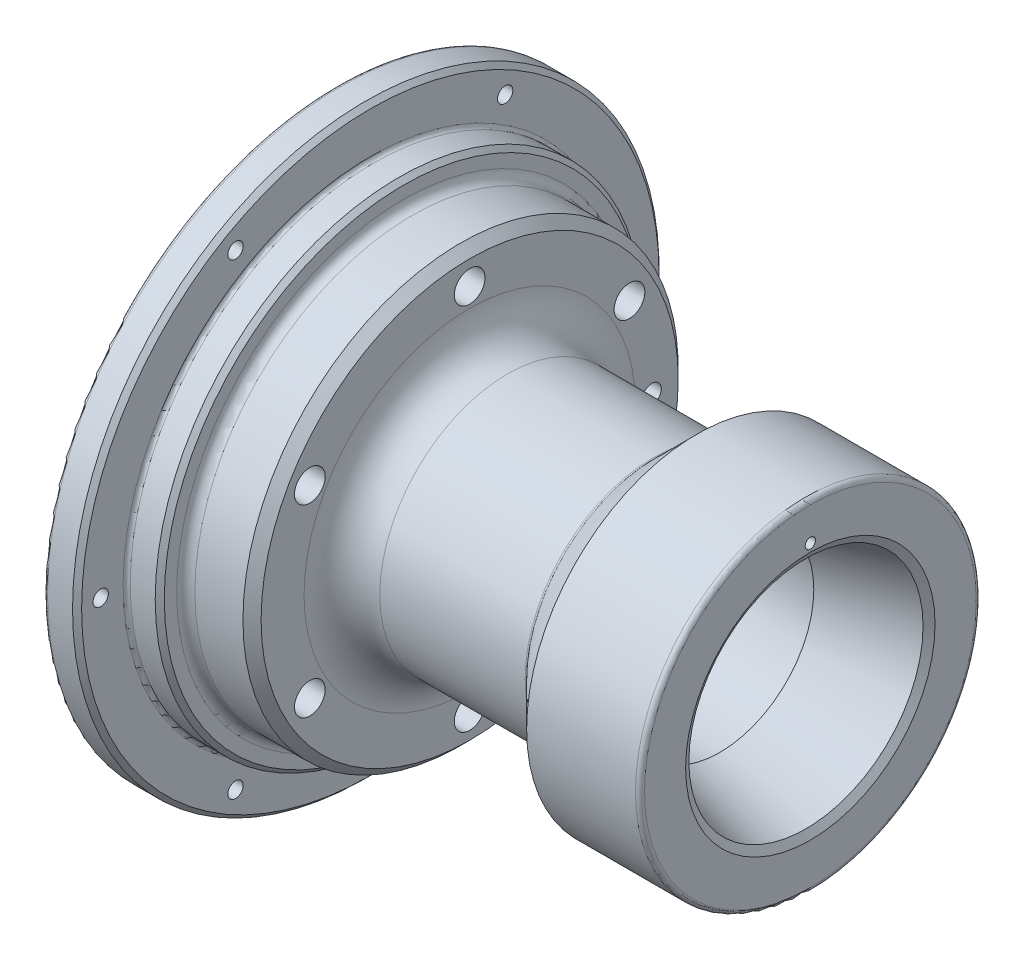
SolidWorks part; units mm, degrees
ref_plane "Front Plane" through (0, 0, 0) normal (0, 0, 1) x (1, 0, 0)
ref_plane "Top Plane" through (0, 0, 0) normal (0, 1, 0) x (1, 0, 0)
ref_plane "Right Plane" through (0, 0, 0) normal (1, 0, 0) x (0, 0, -1)
sketch "Sketch1" plane through (0, 0, 0) normal (0, 1, 0) x (1, 0, 0)
  line L0 (-79.375, 98.3996) -> (-68.2498, 98.3996)
  line L1 (-68.2498, 98.3996) -> (-68.2498, 81.7626)
  line L2 (-68.2498, 81.7626) -> (-57.15, 81.7626)
  line L3 (-57.15, 81.7626) -> (-57.15, 73.025)
  line L4 (-57.15, 73.025) -> (-34.925, 73.025)
  line L5 (-34.925, 73.025) -> (-34.925, 42.8625)
  line L6 (-34.925, 42.8625) -> (27.051, 42.8625)
  line L7 (27.051, 42.8625) -> (41.3385, 57.15)
  line L8 (41.3385, 57.15) -> (79.375, 57.15)
  line L9 (79.375, 57.15) -> (79.375, 39.6877)
  line L10 (79.375, 39.6877) -> (48.9929, 31.5468)
  line L11 (48.9929, 31.5468) -> (-25.273, 31.5468)
  line L12 (-25.273, 31.5468) -> (-25.273, 30.9562)
  line L13 (-25.273, 30.9562) -> (-41.275, 30.9562)
  line L14 (-41.275, 30.9562) -> (-41.275, 34.944)
  line L15 (-41.275, 34.944) -> (-57.1246, 34.944)
  line L16 (-57.1246, 34.944) -> (-57.1246, 53.0085)
  line L17 (-57.1246, 53.0085) -> (-68.2498, 53.0085)
  line L18 (-68.2498, 53.0085) -> (-68.2498, 69.9516)
  line L19 (-68.2498, 69.9516) -> (-79.375, 69.9516)
  line L20 (-79.375, 69.9516) -> (-79.375, 98.3996)
  line L21 (-104.775, 0) -> (104.775, 0) construction
  point P23 (0, 0)
  dimension "D1" = 30.3821
  dimension "D2" = 38.0365
  dimension "D3" = 52.324
  dimension "D4" = 104.648
  dimension "D5" = 114.3
  dimension "D6" = 120.65
  dimension "D7" = 136.4996
  dimension "D8" = 136.525
  dimension "D9" = 147.6248
  dimension "D10" = 158.75
  dimension "D11" = 16.637
  dimension "D12" = 25.3746
  dimension "D13" = 28.448
  dimension "D14" = 41.2496
  dimension "D15" = 45.3911
  dimension "D16" = 55.5371
  dimension "D17" = 58.7119
  dimension "D18" = 63.4556
  dimension "D19" = 66.8528
  dimension "D20" = 67.4434
  dimension "D21" = 98.3996
  dimension "D22" = 79.375
revolve "Revolve1" add sketch "Sketch1" angle 360 about L21
fillet "Fillet1" radius 12.7 1 edges at (-34.925, 0, 42.8625)
fillet "Fillet2" radius 3.048 1 edges at (-57.15, 0, 73.025)
fillet "Fillet3" radius 1.524 1 edges at (79.375, 0, 57.15)
chamfer "Chamfer1" distance 3.048 angle 45 1 edges at (-34.925, 0, 73.025)
hole_wizard "1/4-20 Tapped Hole1" positions "Sketch3" profile "Sketch2" tap size "1/4-20" standard "ANSI Inch"
sketch "Sketch3" plane through (-68.2498, 0, 0) normal (1, 0, 0) x (0, 0, -1)
  line L0 (-90.4748, 0) -> (90.4748, 0) construction
  line L1 (0, 0) -> (90.4748, 0) construction
  circle A0 centre (0, 0) radius 98.3996 construction
  point P0 (-90.4748, 0)
  point P1 (90.4748, 0)
  dimension "D1" = 90.4748
sketch "Sketch2" plane through (-68.2498, 0, 90.4748) normal (0, 1, 0) x (0, 0, -1)
  line L0 (0, 0) -> (0, 12.6743)
  line L1 (0, 12.6743) -> (2.5781, 11.1252)
  line L2 (2.5781, 11.1252) -> (2.5781, 0)
  line L5 (2.5781, 0) -> (0, 0)
  line L10 (0, 12.6743) -> (-2.5781, 11.1252) construction
  line L11 (0, -6.35) -> (0, 107.95) construction
  dimension "Tap Drill Dia." = 5.1562
  dimension "Tap Drill Depth" = 11.1252
  dimension "Drill Angle" = 118
cosmetic thread "Hole Thread1" parameters "D1"=12.7, "D2"=6.35
cosmetic thread "Hole Thread2" parameters "D1"=12.7, "D2"=6.35
hole_wizard "1/4-20 Tapped Hole2" positions "Sketch5" profile "Sketch4" tap size "1/4-20" standard "ANSI Inch"
sketch "Sketch5" plane through (-68.2498, 0, 0) normal (1, 0, 0) x (0, 0, -1)
  line L0 (-45.2374, -78.359) -> (45.2374, -78.359) construction
  line L1 (45.2374, -78.359) -> (45.2374, 78.359) construction
  line L2 (45.2374, 78.359) -> (-45.2374, 78.359) construction
  line L3 (-45.2374, 78.359) -> (-45.2374, -78.359) construction
  line L4 (0, 0) -> (45.2374, -78.359) construction
  circle A0 centre (-90.4748, 0) radius 2.5781 construction
  point P0 (-45.2374, -78.359)
  point P1 (45.2374, -78.359)
  point P3 (-45.2374, 78.359)
  point P5 (45.2374, 78.359)
  dimension "D1" = 45.2374
  dimension "D2" = 135.7122
  dimension "D3" = 78.359
sketch "Sketch4" plane through (-68.2498, -78.359, 45.2374) normal (0, 1, 0) x (0, 0, -1)
  line L0 (0, 0) -> (0, 12.6743)
  line L1 (0, 12.6743) -> (2.5781, 11.1252)
  line L2 (2.5781, 11.1252) -> (2.5781, 0)
  line L5 (2.5781, 0) -> (0, 0)
  line L10 (0, 12.6743) -> (-2.5781, 11.1252) construction
  line L11 (0, -6.35) -> (0, 107.95) construction
  dimension "Tap Drill Dia." = 5.1562
  dimension "Tap Drill Depth" = 11.1252
  dimension "Drill Angle" = 118
cosmetic thread "Hole Thread3" parameters "D1"=12.7, "D2"=6.35
cosmetic thread "Hole Thread4" parameters "D1"=12.7, "D2"=6.35
cosmetic thread "Hole Thread5" parameters "D1"=12.7, "D2"=6.35
cosmetic thread "Hole Thread6" parameters "D1"=12.7, "D2"=6.35
sketch "Sketch6" plane through (0, 0, 0) normal (1, 0, 0) x (0, 0, -1)
  circle A0 centre (0, -61.9252) radius 3.5687
  circle A1 centre (0, 61.9252) radius 3.5687
  point P4 (0, 0)
  dimension "D1" = 7.1374
  dimension "D2" = 7.1374
  dimension "D3" = 123.8504
  dimension "D4" = 61.9252
extrude "Cut-Extrude2" cut sketch "Sketch6" against normal through all from offset 34.925
sketch "Sketch7" plane through (0, 0, 0) normal (1, 0, 0) x (0, 0, -1)
  circle A0 centre (0, -61.9252) radius 5.1562
  circle A1 centre (0, 61.9252) radius 5.1562
  point P4 (0, 0)
  dimension "D1" = 10.3124
  dimension "D2" = 10.3124
  dimension "D3" = 123.8504
  dimension "D4" = 61.9252
extrude "Cut-Extrude4" cut sketch "Sketch7" against normal blind 19.05 from offset 34.925
sketch "Sketch8" plane through (0, 0, 0) normal (1, 0, 0) x (0, 0, -1)
  circle A0 centre (-53.6194, -30.9372) radius 3.5687
  circle A1 centre (53.6194, -30.9372) radius 3.5687
  circle A2 centre (-53.6194, 30.9372) radius 3.5687
  circle A3 centre (53.6194, 30.9372) radius 3.5687
  point P8 (0, 0)
  dimension "D1" = 7.1374
  dimension "D2" = 7.1374
  dimension "D3" = 7.1374
  dimension "D4" = 7.1374
  dimension "D5" = 107.2388
  dimension "D6" = 61.8744
  dimension "D7" = 53.6194
  dimension "D8" = 30.9372
extrude "Cut-Extrude6" cut sketch "Sketch8" against normal through all from offset 34.925
sketch "Sketch9" plane through (0, 0, 0) normal (1, 0, 0) x (0, 0, -1)
  circle A0 centre (-53.6194, -30.9372) radius 5.1562
  circle A1 centre (53.6194, -30.9372) radius 5.1562
  circle A2 centre (-53.6194, 30.9372) radius 5.1562
  circle A3 centre (53.6194, 30.9372) radius 5.1562
  point P8 (0, 0)
  dimension "D1" = 10.3124
  dimension "D2" = 10.3124
  dimension "D3" = 10.3124
  dimension "D4" = 10.3124
  dimension "D5" = 107.2388
  dimension "D6" = 61.8744
  dimension "D7" = 53.6194
  dimension "D8" = 30.9372
extrude "Cut-Extrude8" cut sketch "Sketch9" against normal blind 19.05 from offset 34.925
sketch "Sketch10" plane through (0, 0, 0) normal (1, 0, 0) x (0, 0, -1)
  circle A0 centre (61.1124, 0) radius 3.175
  point P2 (0, 0)
  dimension "D1" = 6.35
  dimension "D2" = 61.1124
extrude "Cut-Extrude10" cut sketch "Sketch10" along normal through all from offset 68.2498
sketch "Sketch11" plane through (0, 0, 0) normal (1, 0, 0) x (0, 0, -1)
  circle A0 centre (61.1124, 0) radius 4.3688
  point P2 (0, 0)
  dimension "D1" = 8.7376
  dimension "D2" = 61.1124
extrude "Cut-Extrude12" cut sketch "Sketch11" along normal blind 15.748 from offset 68.2498
sketch "Sketch12" plane through (0, 0, 0) normal (1, 0, 0) x (0, 0, -1)
  circle A0 centre (61.1124, 0) radius 4.7727
  point P2 (0, 0)
  dimension "D1" = 9.5453
  dimension "D2" = 61.1124
extrude "Cut-Extrude14" cut sketch "Sketch12" along normal blind 14.224 from offset 68.2498
sketch "Sketch13" plane through (0, 0, 0) normal (1, 0, 0) x (0, 0, -1)
  circle A0 centre (0, 44.45) radius 1.7272
  point P2 (0, 0)
  dimension "D1" = 3.4544
  dimension "D2" = 44.45
extrude "Cut-Extrude16" cut sketch "Sketch13" against normal blind 30.226 from offset 79.375
chamfer "Chamfer2" distance 1.524 angle 45 1 edges at (-68.2498, 0, 98.3996)
fillet "Fillet4" radius 1.1938 1 edges at (-79.375, 0, 98.3996)
chamfer "Chamfer3" distance 1.524 angle 45 1 edges at (-41.275, 0, 30.9562)
chamfer "Chamfer4" distance 1.524 angle 45 5 edges at (-57.15, 0, 81.7626) (-79.375, 0, 69.9516) (79.375, 0, 39.6877) (-68.2498, 0, 53.0085) (-57.1246, 0, 34.944)
fillet "Fillet5" radius 1.1938 5 edges at (-41.275, 0, 34.944) (-57.1246, 0, 53.0085) (27.051, 0, 42.8625) (-68.2498, 0, 69.9516) (-68.2498, 0, 81.7626)
